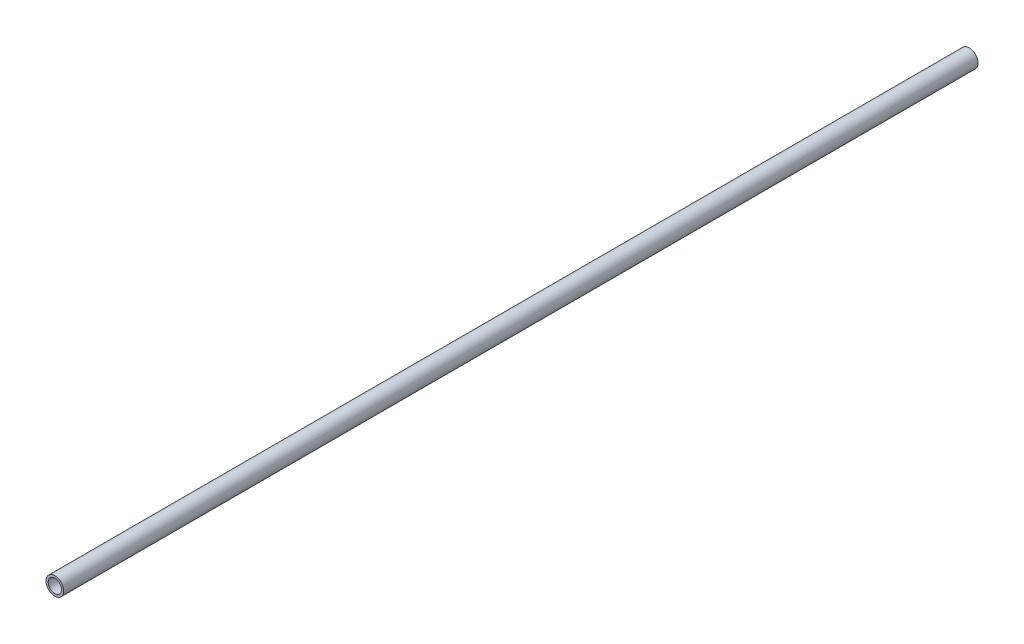
SolidWorks part; units mm, degrees
material "Thornel Mat VMA"
ref_plane "Front Plane" through (0, 0, 0) normal (0, 0, 1) x (1, 0, 0)
ref_plane "Top Plane" through (0, 0, 0) normal (0, 1, 0) x (1, 0, 0)
ref_plane "Right Plane" through (0, 0, 0) normal (1, 0, 0) x (0, 0, -1)
sketch "Sketch1" plane through (0, 0, 0) normal (0, 0, 1) x (1, 0, 0)
  circle A0 centre (0, 0) radius 2
  circle A1 centre (0, 0) radius 1.5
  dimension "D1" = 4
  dimension "D2" = 3
extrude "Boss-Extrude1" add sketch "Sketch1" along normal blind 206.375
